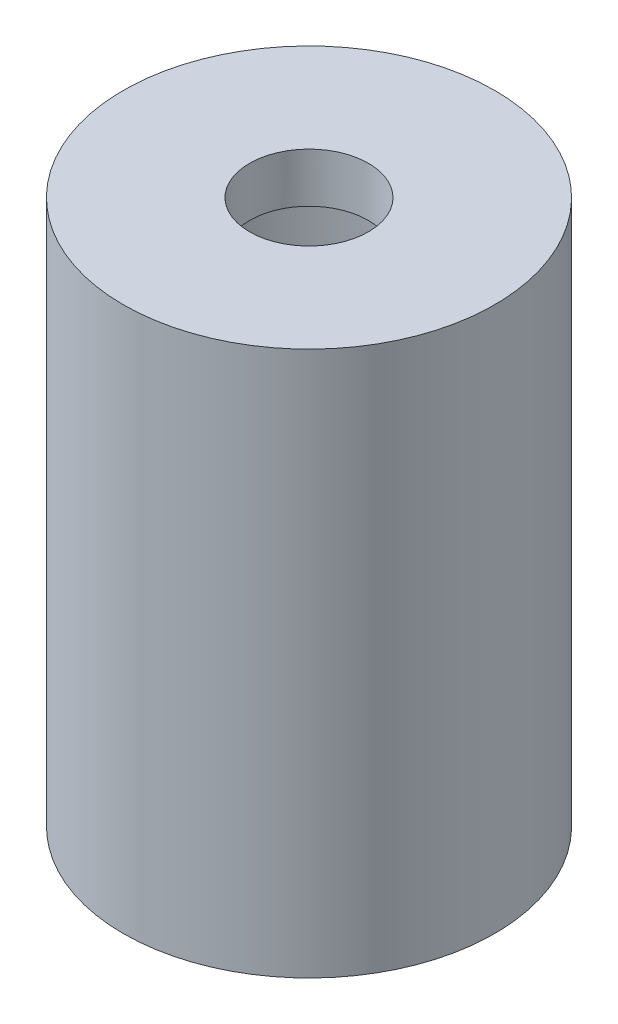
SolidWorks part; units mm, degrees
ref_plane "Front Plane" through (0, 0, 0) normal (0, 0, 1) x (1, 0, 0)
ref_plane "Top Plane" through (0, 0, 0) normal (0, 1, 0) x (1, 0, 0)
ref_plane "Right Plane" through (0, 0, 0) normal (1, 0, 0) x (0, 0, -1)
sketch "Sketch1" plane through (0, 0, 0) normal (0, 0, 1) x (1, 0, 0)
  line L1 (0, 0) -> (37.5, 0)
  line L2 (0, 0) -> (0, 110)
  line L3 (0, 110) -> (37.5, 110)
  line L4 (37.5, 0) -> (37.5, 110)
revolve "Revolve3" add sketch "Sketch1" angle 360 about L4
sketch "Sketch2" plane through (0, 0, 0) normal (0, -1, 0) x (-1, 0, 0)
  line L0 (-75, 0) -> (0, 0)
  circle A1 centre (-37.5, 0) radius 37.5 construction
  circle A2 centre (-37.5, 0) radius 35
  dimension "D1" = 75
  dimension "D2" = 35
extrude "Cut-Extrude2" cut sketch "Sketch2" against normal blind 100 contours L0 A2 | L0 A2
sketch "Sketch3" plane through (0, 110, 0) normal (0, 1, 0) x (1, 0, 0)
  line L0 (0, 0) -> (75, 0)
  circle A1 centre (37.5, 0) radius 37.5 construction
  circle A2 centre (37.5, 0) radius 12
  dimension "D1" = 75
  dimension "D2" = 12
extrude "Cut-Extrude3" cut sketch "Sketch3" against normal through all contours L0 A2 | L0 A2
